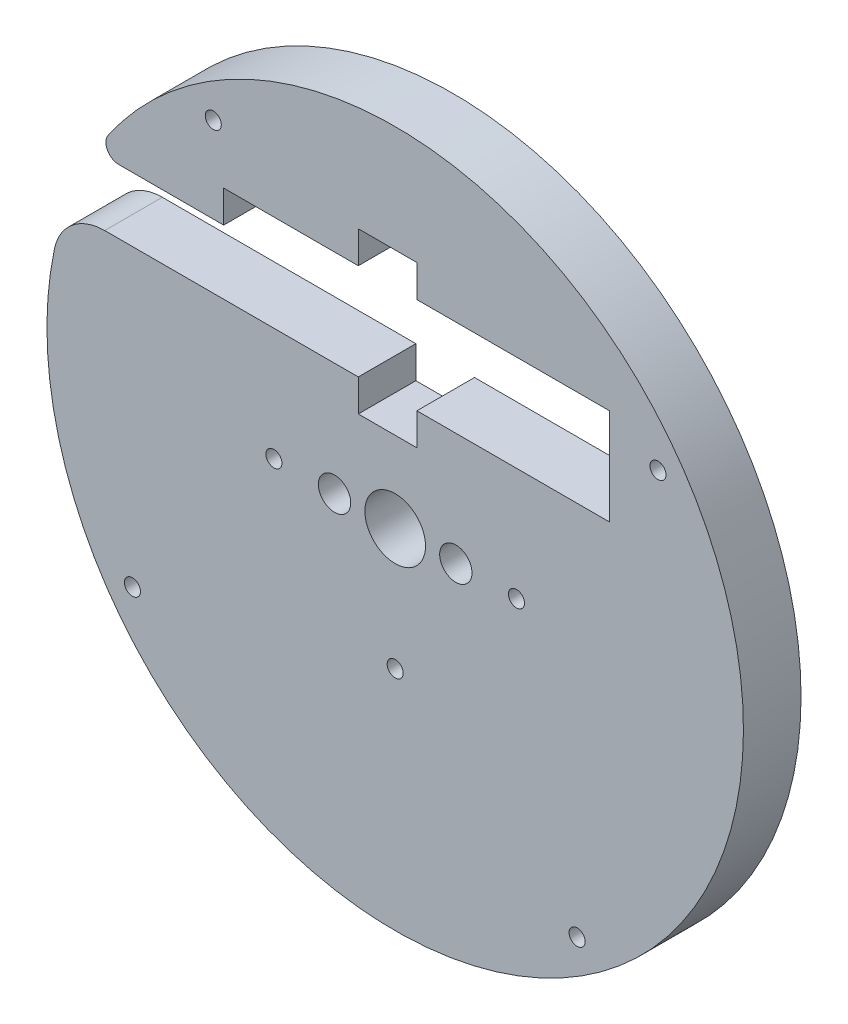
SolidWorks part; units mm, degrees
material "Balsa"
ref_plane "Front Plane" through (0, 0, 0) normal (0, 0, 1) x (1, 0, 0)
ref_plane "Top Plane" through (0, 0, 0) normal (0, 1, 0) x (1, 0, 0)
ref_plane "Right Plane" through (0, 0, 0) normal (1, 0, 0) x (0, 0, -1)
sketch "Sketch1" plane through (0, 0, 0) normal (0, 0, 1) x (1, 0, 0)
  circle A0 centre (0, 0) radius 34.4583
  circle A1 centre (0, 0) radius 3
  dimension "D1" = 68.9167
  dimension "D2" = 6
extrude "Boss-Extrude1" add sketch "Sketch1" along normal blind 5.7
sketch "Sketch3" plane through (0, 0, 5.7) normal (0, 0, 1) x (1, 0, 0)
  line L0 (-3.6521, 11.175) -> (-32.596, 11.175)
  line L1 (-3.6521, 23.875) -> (2.1479, 23.875)
  line L2 (-3.6521, 23.875) -> (-3.6521, 20.7)
  line L3 (-3.6521, 8) -> (2.1479, 8)
  line L4 (2.1479, 23.875) -> (2.1479, 20.7)
  line L5 (-3.6521, 20.7) -> (-16.969, 20.7)
  line L6 (2.1479, 20.7) -> (21.1979, 20.7)
  line L7 (21.1979, 20.7) -> (21.1979, 11.175)
  line L8 (-3.6521, 11.175) -> (-3.6521, 8)
  line L9 (2.1479, 8) -> (2.1479, 11.175)
  line L10 (21.1979, 20.7) -> (27.5479, 20.7) construction
  line L11 (2.1479, 11.175) -> (21.1979, 11.175)
  line L12 (-16.969, 20.7) -> (-16.969, 17.525)
  line L13 (-16.969, 17.525) -> (-29.669, 17.525)
  circle A0 centre (0, 0) radius 34.4583 construction
  arc A1 (-29.669, 17.525) -> (-32.596, 11.175) centre (0, 0) ccw
  dimension "D1" = 15.875
  dimension "D2" = 8
  dimension "D3" = 3.175
  dimension "D4" = 5.8
  dimension "D5" = 19.05
  dimension "D6" = 6.35
  dimension "D7" = 12.7
  dimension "D8" = 3.175
extrude "Cut-Extrude2" cut sketch "Sketch3" against normal through all
fillet "Fillet1" radius 5.08 1 edges at (-32.596, 11.175, 2.85)
fillet "Fillet2" radius 1.27 1 edges at (-29.669, 17.525, 2.85)
sketch "Sketch2" plane through (0, 0, 5.7) normal (0, 0, 1) x (1, 0, 0)
  line L0 (0, 0) -> (0, 12) construction
  line L1 (0, 0) -> (-18, 26) construction
  line L2 (26, 18) -> (0, 0) construction
  line L3 (0, 0) -> (18, -26) construction
  line L5 (0, 0) -> (-26, -18) construction
  line L6 (0, 0) -> (18, -26) construction
  line L7 (0, 0) -> (26, 18) construction
  circle A0 centre (0, 12) radius 0.7937
  circle A1 centre (12, 0) radius 0.7938
  circle A2 centre (0, -12) radius 0.7938
  circle A3 centre (-12, 0) radius 0.7937
  circle A4 centre (0, 0) radius 12 construction
  circle A5 centre (-18, 26) radius 0.7937
  circle A6 centre (26, 18) radius 0.7938
  circle A7 centre (18, -26) radius 0.7937
  circle A8 centre (-26, -18) radius 0.7937
  dimension "D1" = 1.5875
  dimension "D2" = 12
  dimension "D4" = 26
  dimension "D5" = 18
  dimension "D3" = 4
  dimension "D6" = 4
extrude "Cut-Extrude1" cut sketch "Sketch2" against normal through all
hole_wizard "M3 Clearance Hole2" positions "Sketch7" profile "Sketch6" hole size "M3" standard "Ansi Metric"
sketch "Sketch7" plane through (0, 0, 5.7) normal (0, 0, 1) x (1, 0, 0)
  line L0 (0, 0) -> (-6, 0) construction
  line L2 (0, 0) -> (0, 2.6491) construction
  point P15 (-6, 0)
  point P24 (6, 0)
  dimension "D1" = 6
sketch "Sketch6" plane through (-6, 0, 5.7) normal (1, 0, 0) x (0, -1, 0)
  line L0 (0, 0) -> (0, 13.6614)
  line L1 (0, 13.6614) -> (1.6, 12.7)
  line L2 (1.6, 12.7) -> (1.6, 0)
  line L5 (1.6, 0) -> (0, 0)
  line L10 (0, 13.6614) -> (-1.6, 12.7) construction
  line L11 (0, -6.35) -> (0, 107.95) construction
  dimension "Hole Dia." = 3.2
  dimension "Hole Depth" = 12.7
  dimension "Drill Angle" = 118
